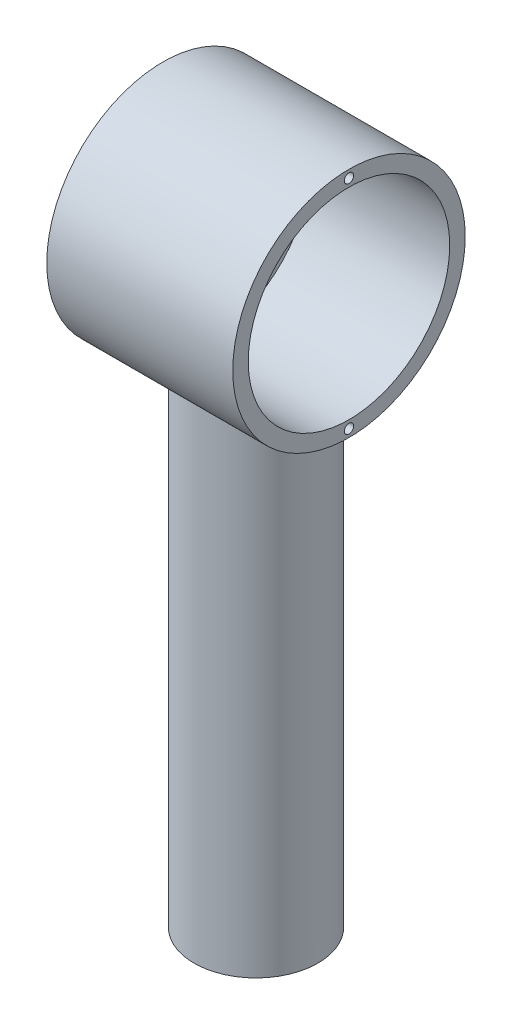
SolidWorks part; units mm, degrees
ref_plane "Front Plane" through (0, 0, 0) normal (0, 0, 1) x (1, 0, 0)
ref_plane "Top Plane" through (0, 0, 0) normal (0, 1, 0) x (1, 0, 0)
ref_plane "Right Plane" through (0, 0, 0) normal (1, 0, 0) x (0, 0, -1)
sketch "Sketch1" plane through (0, 0, 0) normal (0, 1, 0) x (1, 0, 0)
  line L3 (14.4338, 0) -> (7.2169, 12.5)
  line L4 (7.2169, 12.5) -> (-7.2169, 12.5)
  line L5 (-7.2169, 12.5) -> (-14.4338, 0)
  line L6 (-14.4338, 0) -> (-7.2169, -12.5)
  line L7 (-7.2169, -12.5) -> (7.2169, -12.5)
  line L8 (7.2169, -12.5) -> (14.4338, 0)
  circle A0 centre (0, 0) radius 20
  circle A1 centre (0, 0) radius 12.5 construction
  dimension "D1" = 40
extrude "Boss-Extrude1" add sketch "Sketch1" along normal blind 25
sketch "Sketch2" plane through (0, 0, 0) normal (0, -1, 0) x (1, 0, 0)
  circle A1 centre (0, 0) radius 20
extrude "Boss-Extrude2" add sketch "Sketch2" along normal blind 100
ref_plane "Plane1" through (20, 0, 0) normal (1, 0, 0) x (0, 0, -1)
sketch "Sketch5" plane through (0, 0, 0) normal (0, 1, 0) x (1, 0, 0)
  line L1 (14.4338, 0) -> (7.2169, 12.5)
  line L2 (7.2169, 12.5) -> (-7.2169, 12.5)
  line L3 (-7.2169, 12.5) -> (-14.4338, 0)
  line L4 (-14.4338, 0) -> (-7.2169, -12.5)
  line L5 (-7.2169, -12.5) -> (7.2169, -12.5)
  line L6 (7.2169, -12.5) -> (14.4338, 0)
  circle A0 centre (0, 0) radius 12.5 construction
sketch "Sketch6" plane through (0, 25, 0) normal (0, 1, 0) x (1, 0, 0)
  circle A0 centre (0, 0) radius 20
  dimension "D1" = 40
extrude "Boss-Extrude4" add sketch "Sketch6" against normal blind 100
sketch "Sketch7" plane through (20, 0, 0) normal (1, 0, 0) x (0, 0, -1)
  circle A2 centre (0, 39.2866) radius 25
  dimension "D3" = 50
extrude "Cut-Extrude2" cut sketch "Sketch7" against normal blind 40
sketch "Sketch8" plane through (20, 0, 0) normal (1, 0, 0) x (0, 0, -1)
  circle A0 centre (0, 39.2528) radius 25
  circle A1 centre (0, 39.2528) radius 22.5
  dimension "D1" = 50
  dimension "D2" = 45
extrude "Boss-Extrude7" add sketch "Sketch8" against normal blind 40 contours A1 | A0
sketch "Sketch9" plane through (20, 0, 0) normal (1, 0, 0) x (0, 0, -1)
  circle A0 centre (0, 39.2528) radius 25
extrude "Boss-Extrude8" add sketch "Sketch9" against normal blind 2
sketch "Sketch10" plane through (18, 0, 0) normal (-1, 0, 0) x (0, 0, 1)
  line L1 (-15.0811, 22.5552) -> (15.0811, 22.5552)
  arc A1 (-15.0811, 22.5552) -> (15.0811, 22.5552) centre (0, 39.2528) ccw
extrude "Boss-Extrude10" add sketch "Sketch10" along normal blind 38
sketch "Sketch11" plane through (0, -100, 0) normal (0, -1, 0) x (1, 0, 0)
  line L0 (0, 20) -> (0, 0)
  line L1 (0, 0) -> (20, 0)
  line L2 (20, -27.5) -> (20, 27.5) construction
  line L4 (0, 14.4338) -> (-12.5, 7.2169)
  line L5 (-12.5, 7.2169) -> (-12.5, -7.2169)
  line L6 (-12.5, -7.2169) -> (0, -14.4338)
  line L7 (0, -14.4338) -> (12.5, -7.2169)
  line L8 (12.5, -7.2169) -> (12.5, 7.2169)
  line L9 (12.5, 7.2169) -> (0, 14.4338)
  arc A0 (20, 0) -> (-20, 0) centre (0, 0) ccw construction
  circle A1 centre (0, 0) radius 12.5 construction
extrude "Cut-Extrude3" cut sketch "Sketch11" against normal blind 25 contours L8 L9 L0 L1 | L7 L8 L1 L0 L4 L5 L6
sketch "Sketch12" plane through (20, 0, 0) normal (1, 0, 0) x (0, 0, -1)
  circle A0 centre (0, 39.2528) radius 25
extrude "Cut-Extrude4" cut sketch "Sketch12" against normal blind 75
sketch "Sketch13" plane through (20, 0, 0) normal (1, 0, 0) x (0, 0, -1)
  circle A0 centre (0, 39.3347) radius 37.5
  dimension "D1" = 75
sketch "Sketch14" plane through (0, -100, 0) normal (0, -1, 0) x (1, 0, 0)
  line L1 (0, -14.4338) -> (12.5, -7.2169)
  line L2 (12.5, -7.2169) -> (12.5, 7.2169)
  line L3 (12.5, 7.2169) -> (0, 14.4338)
  line L4 (0, 14.4338) -> (-12.5, 7.2169)
  line L5 (-12.5, 7.2169) -> (-12.5, -7.2169)
  line L6 (-12.5, -7.2169) -> (0, -14.4338)
  circle A0 centre (0, 0) radius 12.5 construction
  circle A1 centre (0, 0) radius 20
extrude "Boss-Extrude11" add sketch "Sketch14" along normal blind 50
extrude "Boss-Extrude12" add sketch "Sketch13" against normal blind 50 and the other way blind 10
sketch "Sketch16" plane through (30, 0, 0) normal (1, 0, 0) x (0, 0, -1)
  line L0 (-17.3205, 17.3347) -> (17.3205, 17.3347)
  line L1 (0, 67.3347) -> (24.1903, 67.3347)
  circle A0 centre (0, 39.3347) radius 28
  dimension "D1" = 56
  dimension "D2" = 50
sketch "Sketch17" plane through (30, 0, 0) normal (1, 0, 0) x (0, 0, -1)
  circle A0 centre (0, 39.3347) radius 32.5
  dimension "D1" = 65
extrude "Cut-Extrude5" cut sketch "Sketch17" against normal blind 50 contours A0
sketch "Sketch18" plane through (30, 0, 0) normal (1, 0, 0) x (0, 0, -1)
  circle A0 centre (0, 39.3347) radius 32.5
  circle A1 centre (0, 39.3347) radius 37.5
extrude "Boss-Extrude13" add sketch "Sketch18" along normal blind 2
sketch "Sketch19" plane through (32, 0, 0) normal (1, 0, 0) x (0, 0, -1)
  line L0 (0, 71.8347) -> (0, 76.8347)
  line L1 (0, 76.8347) -> (0, 74.3347)
  line L2 (0, 74.3347) -> (3.9271, 74.3347)
  line L3 (0, 6.8347) -> (0, 1.8347)
  line L4 (0, 1.8347) -> (0, 4.3347)
  line L5 (0, 4.3347) -> (3.9271, 4.3347)
  circle A0 centre (0, 39.3347) radius 32.5 construction
  circle A1 centre (0, 39.3347) radius 32.5 construction
  circle A2 centre (0, 39.3347) radius 37.5 construction
  arc A3 (-20, 7.6133) -> (20, 7.6133) centre (0, 39.3347) ccw construction
sketch "Sketch21" plane through (32, 0, 0) normal (1, 0, 0) x (0, 0, -1)
  circle A0 centre (0, 39.3347) radius 32.5
  circle A1 centre (0, 39.3347) radius 37.5
extrude "Cut-Extrude6" cut sketch "Sketch21" against normal blind 2
sketch "Sketch22" plane through (30, 0, 0) normal (1, 0, 0) x (0, 0, -1)
  circle A0 centre (0, 74.3347) radius 1.5
  circle A1 centre (0, 4.3347) radius 1.5
  dimension "D1" = 3
  dimension "D2" = 3
extrude "Cut-Extrude7" cut sketch "Sketch22" against normal blind 10
sketch "Sketch23" plane through (-20, 0, 0) normal (1, 0, 0) x (0, 0, -1)
  line L0 (0, 71.8347) -> (0, 66.8347)
  dimension "D1" = 5
sketch "Sketch26" plane through (-20, 0, 0) normal (1, 0, 0) x (0, 0, -1)
  circle A0 centre (0, 66.8347) radius 0.4
  dimension "D1" = 0.8
sketch "Sketch27" plane through (-20, 0, 0) normal (1, 0, 0) x (0, 0, -1)
  circle A0 centre (0, 39.3347) radius 32.5
  dimension "D1" = 65
extrude "Boss-Extrude14" add sketch "Sketch27" along normal blind 5
